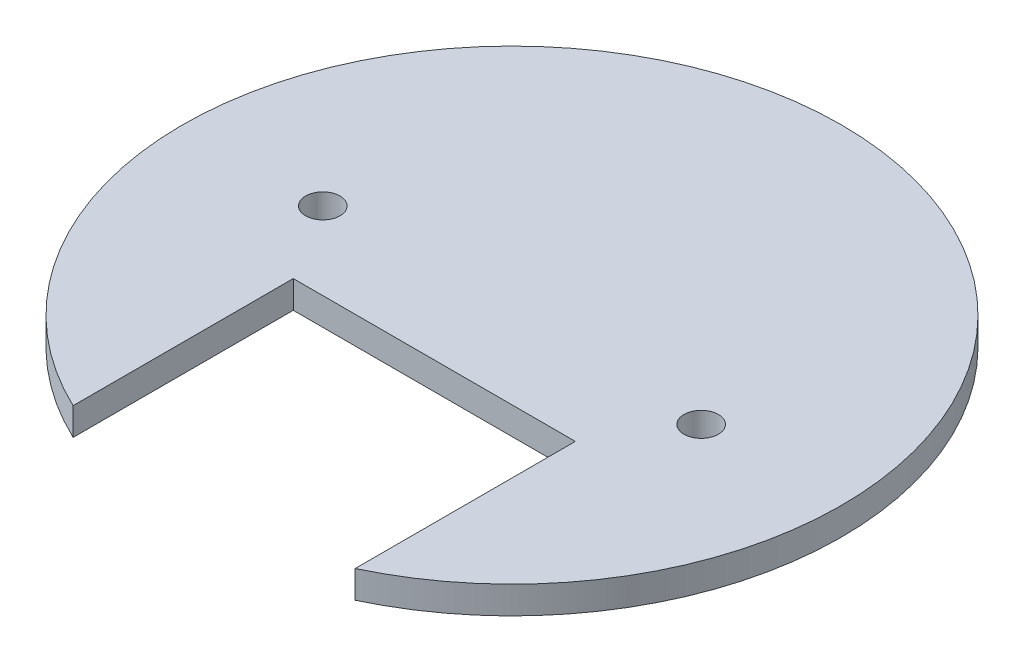
SolidWorks part; units mm, degrees
ref_plane "Front Plane" through (0, 0, 0) normal (0, 0, 1) x (1, 0, 0)
ref_plane "Top Plane" through (0, 0, 0) normal (0, 1, 0) x (1, 0, 0)
ref_plane "Right Plane" through (0, 0, 0) normal (1, 0, 0) x (0, 0, -1)
sketch "Sketch1" plane through (0, 0, 0) normal (0, 1, 0) x (1, 0, 0)
  line L0 (-47.9, 0) -> (47.9, 0) construction
  line L1 (0, 47.9) -> (0, -47.75) construction
  line L2 (-20.5, -43.2916) -> (-20.5, -11.2916)
  line L3 (-20.5, -11.2916) -> (20.5, -11.2916)
  line L4 (20.5, -11.2916) -> (20.5, -43.2916)
  arc A0 (20.5, -43.2916) -> (-20.5, -43.2916) centre (0, 0) ccw
  circle A1 centre (-27.5, 0) radius 2.5
  circle A2 centre (27.5, 0) radius 2.5
  dimension "D1" = 95.8
  dimension "D2" = 5
  dimension "D3" = 55
  dimension "D4" = 32
  dimension "D5" = 41
extrude "Boss-Extrude2" add sketch "Sketch1" along normal blind 4
